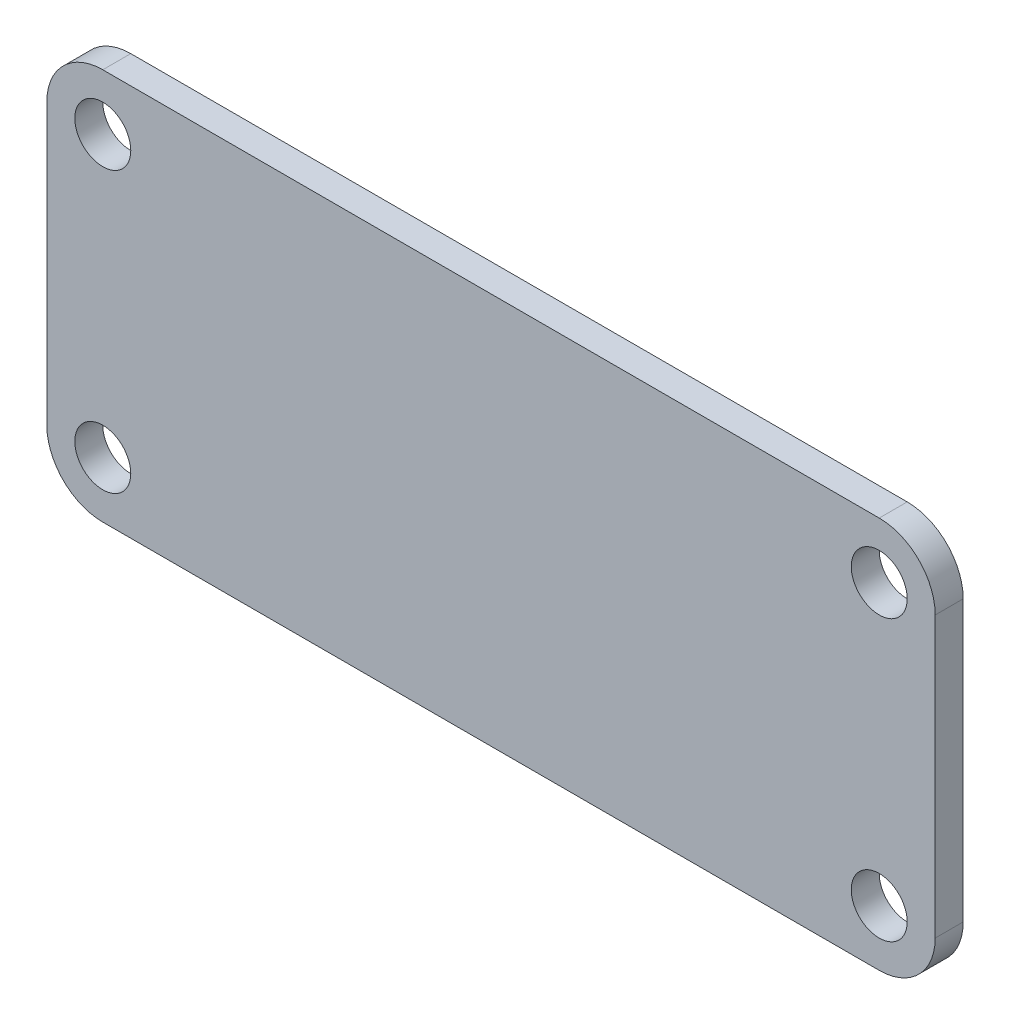
SolidWorks part; units mm, degrees
ref_plane "前视基准面" through (0, 0, 0) normal (0, 0, 1) x (1, 0, 0)
ref_plane "上视基准面" through (0, 0, 0) normal (0, 1, 0) x (1, 0, 0)
ref_plane "右视基准面" through (0, 0, 0) normal (1, 0, 0) x (0, 0, -1)
sketch "草图1" plane through (0, 0, 0) normal (0, 0, 1) x (1, 0, 0)
  line L1 (-138.745, 70) -> (138.745, 70)
  line L2 (-158.745, 50) -> (-158.745, -50)
  line L3 (-138.745, -70) -> (138.745, -70)
  line L4 (158.745, 50) -> (158.745, -50)
  line L5 (-158.745, 70) -> (158.745, -70) construction
  line L6 (-158.745, -70) -> (158.745, 70) construction
  arc A0 (138.745, 70) -> (158.745, 50) centre (138.745, 50) cw
  arc A1 (138.745, -70) -> (158.745, -50) centre (138.745, -50) ccw
  arc A2 (-158.745, -50) -> (-138.745, -70) centre (-138.745, -50) ccw
  arc A3 (-158.745, 50) -> (-138.745, 70) centre (-138.745, 50) cw
  circle A4 centre (-138.745, 50) radius 10
  circle A5 centre (-138.745, -50) radius 10
  circle A6 centre (138.745, -50) radius 10
  circle A7 centre (138.745, 50) radius 10
  point P0 (0, 0)
  dimension "D1" = 20
  dimension "D4" = 20
  dimension "D5" = 20
  dimension "D6" = 20
  dimension "D7" = 20
  dimension "D2" = 277.49
  dimension "D3" = 100
extrude "凸台-拉伸1" add sketch "草图1" along normal blind 10
